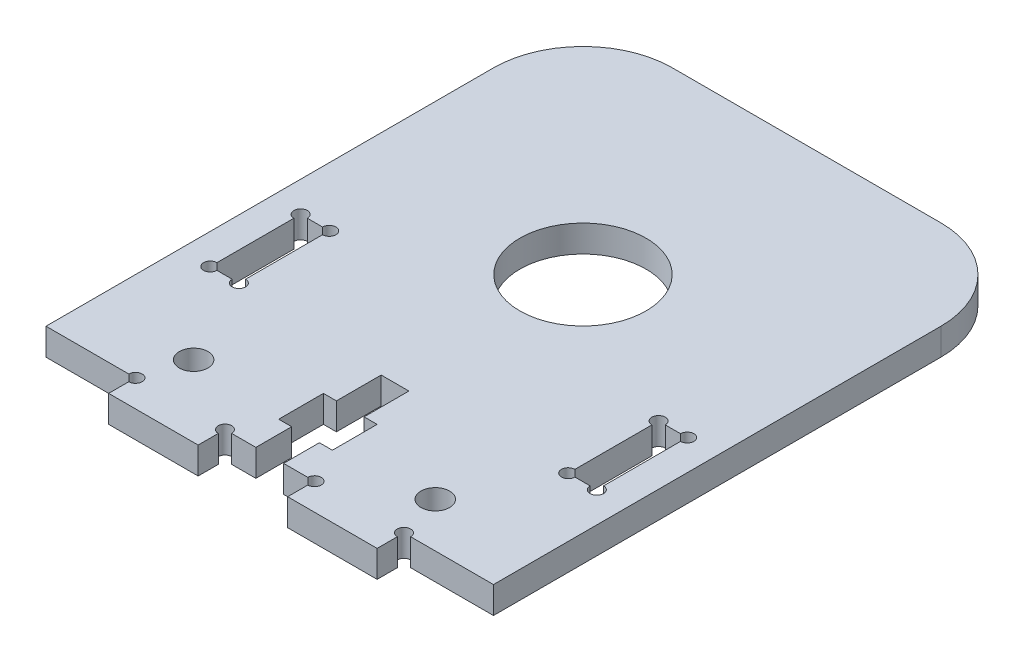
SolidWorks part; units mm, degrees
ref_plane "前视基准面" through (0, 0, 0) normal (0, 0, 1) x (1, 0, 0)
ref_plane "上视基准面" through (0, 0, 0) normal (0, 1, 0) x (1, 0, 0)
ref_plane "右视基准面" through (0, 0, 0) normal (1, 0, 0) x (0, 0, -1)
other "Configuration Table"
sketch "草图1" plane through (0, 0, 0) normal (0, 1, 0) x (1, 0, 0)
  line L1 (-25, -30) -> (25, -30)
  line L2 (-25, -30) -> (-25, 30)
  line L3 (-25, 30) -> (25, 30)
  line L4 (25, -30) -> (25, 30)
  line L5 (-25, -30) -> (25, 30) construction
  line L6 (-25, 30) -> (25, -30) construction
  point P0 (0, 0)
  dimension "D1" = 50
  dimension "D2" = 60
extrude "凸台-拉伸1" add sketch "草图1" along normal blind 3
sketch "草图2" plane through (0, 3, 0) normal (0, 1, 0) x (1, 0, 0)
  line L0 (0, 0) -> (0, -45.2545) construction
  line L1 (-25, -30) -> (25, -30) construction
  line L2 (-15, -30) -> (-5, -30)
  line L3 (-15, -30) -> (-15, -33)
  line L4 (-15, -33) -> (-5, -33)
  line L5 (-5, -30) -> (-5, -33)
  line L6 (-10, -33) -> (-10, -30) construction
  line L7 (15, -33) -> (5, -33)
  line L8 (5, -30) -> (5, -33)
  line L9 (15, -30) -> (5, -30)
  line L10 (15, -30) -> (15, -33)
  dimension "D1" = 3
  dimension "D2" = 10
  dimension "D3" = 10
extrude "凸台-拉伸2" add sketch "草图2" against normal blind 3
sketch "草图3" plane through (0, 3, 0) normal (0, 1, 0) x (1, 0, 0)
  line L0 (0, 0) -> (0, -32.9862) construction
  line L1 (-1.55, -30) -> (-1.55, -26)
  line L2 (-5, -30) -> (5, -30) construction
  line L3 (-1.55, -26) -> (-3, -26)
  line L4 (-3, -26) -> (-3, -21)
  line L5 (-3, -21) -> (-1.55, -21)
  line L6 (-1.55, -21) -> (-1.55, -16)
  line L7 (-1.55, -16) -> (1.55, -16)
  line L8 (-1.55, -30) -> (1.55, -30)
  line L9 (1.55, -30) -> (1.55, -26)
  line L10 (1.55, -26) -> (3, -26)
  line L11 (3, -26) -> (3, -21)
  line L12 (3, -21) -> (1.55, -21)
  line L13 (1.55, -21) -> (1.55, -16)
  line L14 (25, -30) -> (25, 30) construction
  point P12 (0, -30)
  point P19 (0, -16)
  dimension "D1" = 5
  dimension "D2" = 4
  dimension "D3" = 5
  dimension "D4" = 3
  dimension "D5" = 3.1
  dimension "D6" = 3.1
extrude "切除-拉伸1" cut sketch "草图3" against normal through all
sketch "草图4" plane through (0, 3, 0) normal (0, 1, 0) x (1, 0, 0)
  line L0 (25, -30) -> (25, 30) construction
  line L1 (-25, -30) -> (-15, -30) construction
  circle A0 centre (0, 5) radius 7.05
  point P2 (0, 0)
  dimension "D1" = 14.1
  dimension "D2" = 35
  dimension "D3" = 25
extrude "切除-拉伸2" cut sketch "草图4" against normal through all
sketch "草图5" plane through (0, 0, 0) normal (0, -1, 0) x (1, 0, 0)
  line L0 (0, 0) -> (0, -3.0079) construction
  line L1 (20, 15.05) -> (20, 4.95) construction
  line L2 (18.4, 15.05) -> (21.6, 15.05)
  line L3 (18.4, 15.05) -> (18.4, 4.95)
  line L4 (18.4, 4.95) -> (21.6, 4.95)
  line L5 (21.6, 15.05) -> (21.6, 4.95)
  line L6 (18.4, 10) -> (21.6, 10) construction
  line L7 (25, 30) -> (25, -30) construction
  line L8 (15, 30) -> (25, 30) construction
  line L9 (-18.4, 4.95) -> (-21.6, 4.95)
  line L10 (-21.6, 15.05) -> (-21.6, 4.95)
  line L11 (-18.4, 15.05) -> (-21.6, 15.05)
  line L12 (-18.4, 15.05) -> (-18.4, 4.95)
  circle A0 centre (13.5, 25) radius 1.6
  circle A1 centre (-13.5, 25) radius 1.6
  point P13 (20, 10)
  dimension "D5" = 3.2
  dimension "D1" = 10.1
  dimension "D2" = 3.2
  dimension "D3" = 5
  dimension "D4" = 20
  dimension "D6" = 5
  dimension "D7" = 6.5
extrude "切除-拉伸3" cut sketch "草图5" against normal through all
sketch "草图7" plane through (0, 0, 0) normal (0, -1, 0) x (1, 0, 0)
  line L0 (0, 0) -> (0, 5.9238) construction
  circle A0 centre (-21.6, 15.05) radius 0.75
  circle A1 centre (-18.4, 15.05) radius 0.75
  circle A2 centre (-18.4, 4.95) radius 0.75
  circle A3 centre (-21.6, 4.95) radius 0.75
  circle A4 centre (21.6, 4.95) radius 0.75
  circle A5 centre (18.4, 4.95) radius 0.75
  circle A6 centre (18.4, 15.05) radius 0.75
  circle A7 centre (21.6, 15.05) radius 0.75
  circle A8 centre (-15, 30) radius 0.75
  circle A9 centre (-5, 30) radius 0.75
  circle A10 centre (5, 30) radius 0.75
  circle A11 centre (15, 30) radius 0.75
  dimension "D1" = 1.5
  dimension "D2" = 1.5
extrude "切除-拉伸4" cut sketch "草图7" against normal through all
fillet "圆角1" radius 10 2 edges at (25, 1.5, -30) (-25, 1.5, -30)
